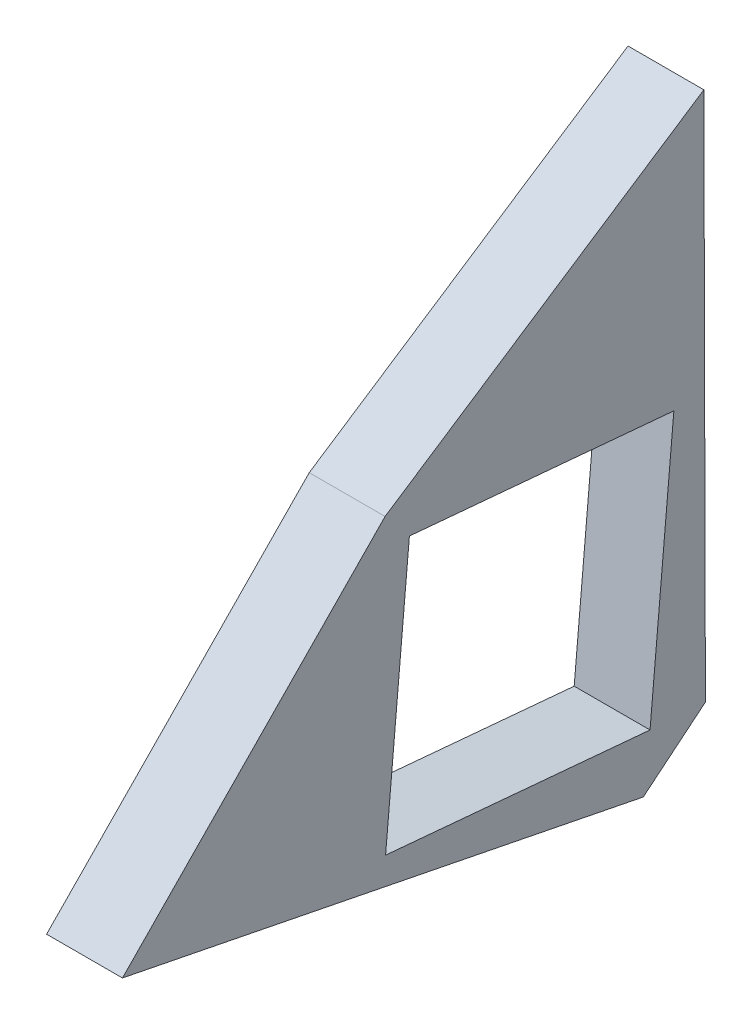
SolidWorks part; units mm, degrees
material "Сосна"
ref_plane "Спереди" through (0, 0, 0) normal (0, 0, 1) x (1, 0, 0)
ref_plane "Сверху" through (0, 0, 0) normal (0, 1, 0) x (1, 0, 0)
ref_plane "Справа" through (0, 0, 0) normal (1, 0, 0) x (0, 0, -1)
sketch3d "Трехмерный эскиз1"
  line L10 (0, 18.4597, -6.5915) -> (0, 7.3822, 10.2164)
  line L11 (0, 18.4597, -6.5915) -> (0, -9.5402, -6.6726)
  line L16 (0, -9.5402, -6.6726) -> (0, -12.236, -3.3964)
  line L17 (0, -12.236, -3.3964) -> (0, -6.7693, 24.0647)
  line L22 (0, 7.3822, 10.2164) -> (0, -6.7693, 24.0647)
  line L23 (0, 5.8468, 8.9348) -> (0, -8.0968, 10.1907)
  line L28 (0, 4.5908, -5.0088) -> (0, 5.8468, 8.9348)
  line L29 (0, 4.5908, -5.0088) -> (0, -9.3527, -3.7528)
  line L34 (0, -9.3527, -3.7528) -> (0, -8.0968, 10.1907)
  point P114 (-83.3137, -1.0149, -16.6463)
  point P263 (-83.8457, 0, -14.1783)
  point P264 (-83.8457, 0, -14.1783)
  point P265 (-83.8457, 0, -14.1783)
  point P267 (-80.8457, 0, 24.8217)
  dimension "D1" = 20.13
  dimension "D2" = 19.8
  dimension "D3" = 28
  dimension "D4" = 28
  dimension "D5" = 4.2426
  dimension "D7" = 2
  dimension "D8" = 14
  dimension "D9" = 14
extrude "Бобышка-Вытянуть1" add sketch "Трехмерный эскиз1" along direction (1, 0, 0) on the side of the normal blind 4
